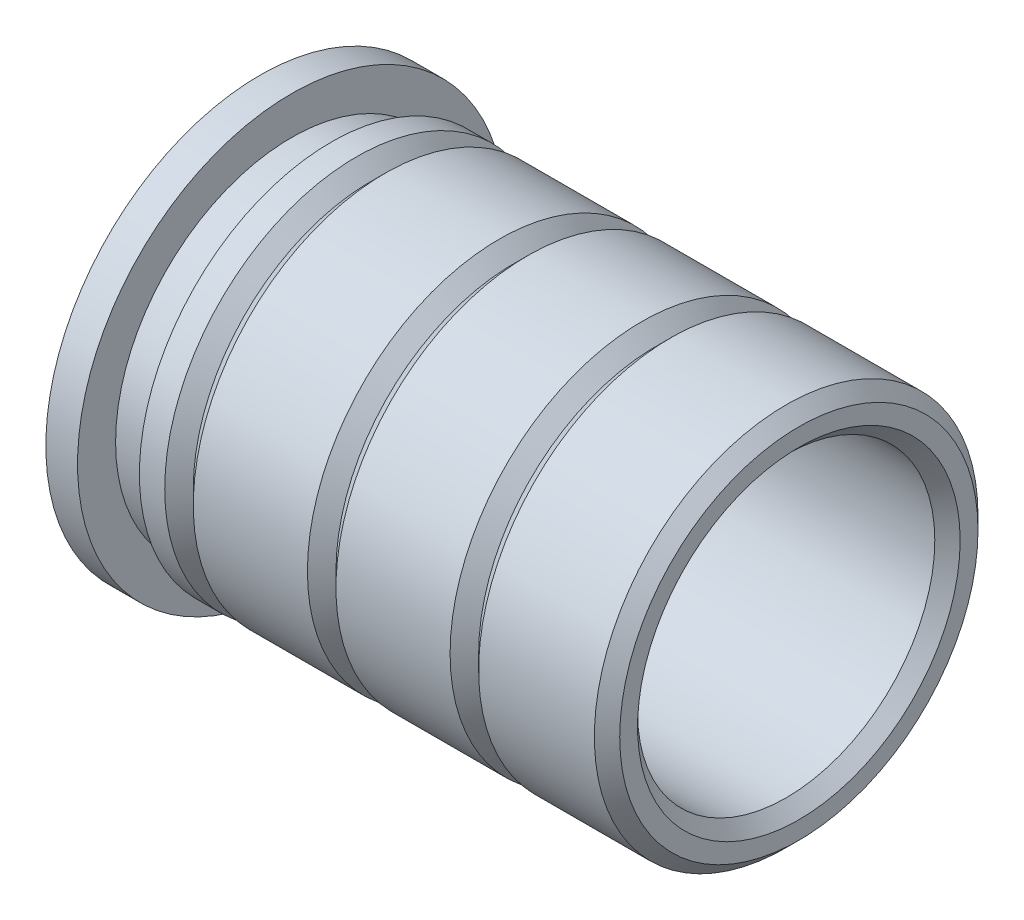
SolidWorks part; units mm, degrees
material "Tin Bearing Bronze"
ref_plane "Front Plane" through (0, 0, 0) normal (0, 0, 1) x (1, 0, 0)
ref_plane "Top Plane" through (0, 0, 0) normal (0, 1, 0) x (1, 0, 0)
ref_plane "Right Plane" through (0, 0, 0) normal (1, 0, 0) x (0, 0, -1)
sketch "Sketch1" plane through (0, 0, 0) normal (0, 0, 1) x (1, 0, 0)
  line L0 (0, 0) -> (-13.8087, 0) construction
  line L1 (0, 2.3813) -> (8.636, 2.3813)
  line L2 (0, 2.3813) -> (0, 3.429)
  line L3 (0, 3.429) -> (0.508, 3.429)
  line L4 (8.636, 2.3813) -> (8.636, 3.0734)
  line L5 (0.508, 3.429) -> (0.508, 2.8194)
  line L6 (0.508, 2.8194) -> (1.143, 2.8194)
  line L7 (1.143, 2.8194) -> (1.143, 3.0734)
  line L8 (1.143, 3.0734) -> (8.636, 3.0734)
  dimension "D1" = 4.7625
  dimension "D2" = 6.858
  dimension "D3" = 8.636
  dimension "D4" = 6.1468
  dimension "D5" = 0.508
  dimension "D6" = 0.635
  dimension "D7" = 0.254
revolve "Revolve1" add sketch "Sketch1" angle 360 about L0
chamfer "Chamfer1" distance 0.2032 angle 45 2 edges at (0, 0, -2.3813) (8.636, 0, -2.3813)
chamfer "Chamfer2" distance 0.2032 angle 45 1 edges at (8.636, 0, -3.0734)
sketch "Sketch2" plane through (0, 0, 0) normal (0, 0, 1) x (1, 0, 0)
  line L0 (1.2623, 3.3605) -> (1.778, 2.8448)
  line L1 (1.778, 2.8448) -> (2.2937, 3.3605)
  line L2 (2.2937, 3.3605) -> (1.2623, 3.3605)
  line L3 (1.778, 2.8448) -> (1.778, 4.2293) construction
  line L4 (0, 0) -> (-1.2174, 0) construction
  line L5 (0, 3.429) -> (0, -3.429) construction
  dimension "D1" = 90
  dimension "D2" = 45
  dimension "D3" = 2.8448
  dimension "D4" = 1.778
revolve "Cut-Revolve1" cut sketch "Sketch2" angle 360 about L4
pattern_linear "LPattern1" count 3 spacing 2.286 along (1, 0, 0) of "Cut-Revolve1"
